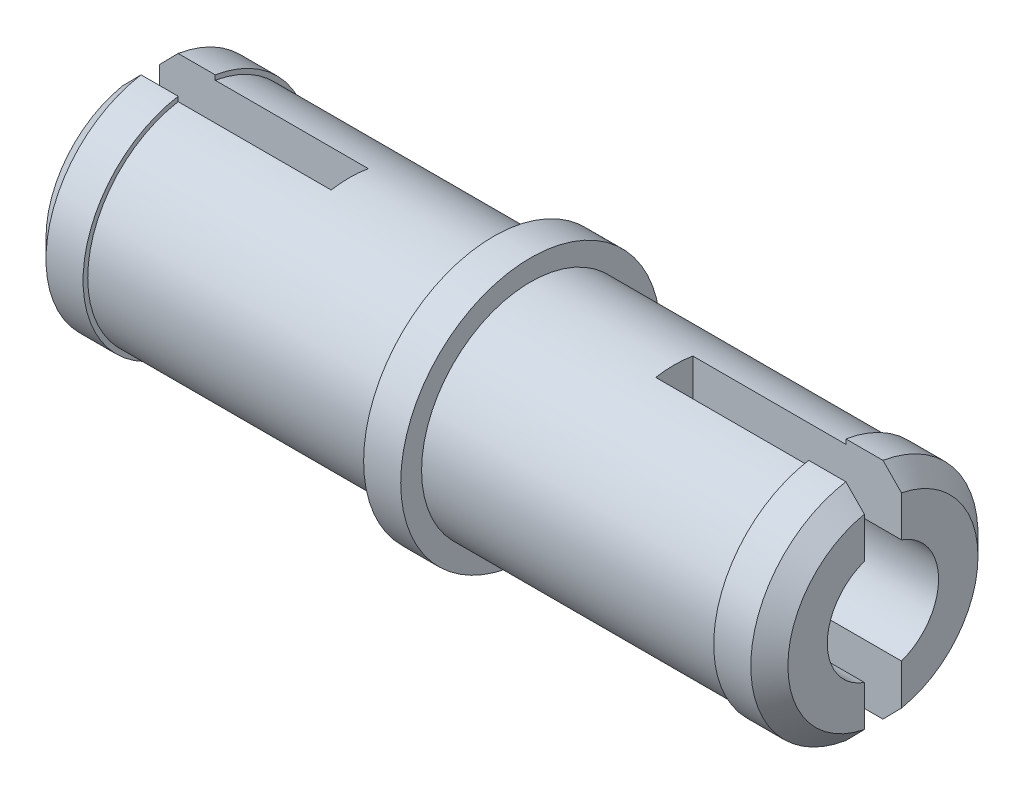
SolidWorks part; units mm, degrees
ref_plane "Front Plane" through (0, 0, 0) normal (0, 0, 1) x (1, 0, 0)
ref_plane "Top Plane" through (0, 0, 0) normal (0, 1, 0) x (1, 0, 0)
ref_plane "Right Plane" through (0, 0, 0) normal (1, 0, 0) x (0, 0, -1)
sketch "Sketch1" plane through (0, 0, 0) normal (0, 0, 1) x (1, 0, 0)
  line L0 (-8, 0) -> (8, 0) construction
  line L1 (-8, 0) -> (-8, 2.45)
  line L2 (-8, 2.45) -> (-6.8, 2.45)
  line L3 (-6.8, 2.45) -> (-6.8, 2.35)
  line L4 (-6.8, 2.35) -> (-0.4, 2.35)
  line L5 (-0.4, 2.35) -> (-0.4, 2.8)
  line L6 (-0.4, 2.8) -> (0.4, 2.8)
  line L7 (0.4, 2.8) -> (0.4, 2.35)
  line L8 (0.4, 2.35) -> (6.8, 2.35)
  line L9 (6.8, 2.35) -> (6.8, 2.45)
  line L10 (6.8, 2.45) -> (8, 2.45)
  line L11 (8, 2.45) -> (8, 0)
  line L12 (8, 0) -> (-8, 0)
  point P4 (0, 0)
  dimension "D1" = 16
  dimension "D2" = 2.45
  dimension "D3" = 1.2
  dimension "D4" = 0.1
  dimension "D5" = 6.4
  dimension "D6" = 0.45
  dimension "D7" = 0.8
revolve "Revolve1" add sketch "Sketch1" angle 360 about L0
sketch "Sketch2" plane through (0, 0, 0) normal (0, 1, 0) x (1, 0, 0)
  line L0 (-9.1343, 0) -> (9.1343, 0) construction
  line L1 (-8, 2.45) -> (-8, -2.45) construction
  line L2 (-10.4106, 0.4) -> (-3.5, 0.4)
  line L3 (-10.4106, 0.4) -> (-10.4106, -0.4)
  line L4 (-10.4106, -0.4) -> (-3.5, -0.4)
  line L5 (-3.5, 0.4) -> (-3.5, -0.4)
  line L6 (-10.4106, 0.4) -> (-3.5, -0.4) construction
  line L7 (-10.4106, -0.4) -> (-3.5, 0.4) construction
  line L8 (9.5172, 0.4) -> (3.5, 0.4)
  line L9 (9.5172, 0.4) -> (9.5172, -0.4)
  line L10 (9.5172, -0.4) -> (3.5, -0.4)
  line L11 (3.5, 0.4) -> (3.5, -0.4)
  line L12 (9.5172, 0.4) -> (3.5, -0.4) construction
  line L13 (9.5172, -0.4) -> (3.5, 0.4) construction
  line L14 (8, -2.45) -> (8, 2.45) construction
  point P0 (-6.9553, 0)
  point P4 (0, 0)
  point P10 (6.5086, 0)
  dimension "D1" = 0.8
  dimension "D2" = 4.5
  dimension "D3" = 0.8
  dimension "D4" = 4.5
extrude "Cut-Extrude1" cut sketch "Sketch2" against normal through all both and the other way through all
chamfer "Chamfer1" distance 0.4 angle 45 4 edges at (-8, 0, -2.45) (-8, 0, 2.45) (8, 0, -2.45) (8, 0, 2.45)
sketch "Sketch3" plane through (8, 0, 0) normal (1, 0, 0) x (0, 0, -1)
  circle A0 centre (0, 0) radius 1.2
  dimension "D1" = 2.4
extrude "Cut-Extrude2" cut sketch "Sketch3" against normal through all and the other way through all
